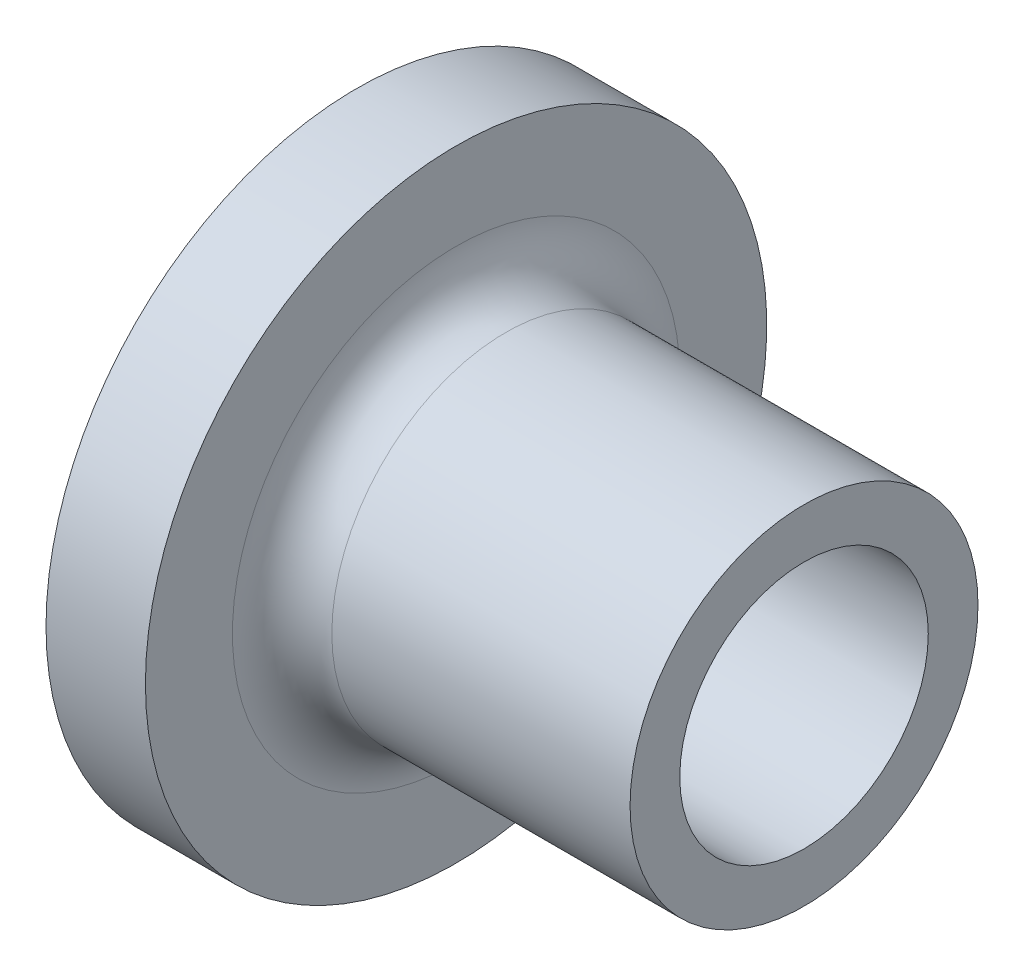
SolidWorks part; units mm, degrees
ref_plane "Front Plane" through (0, 0, 0) normal (0, 0, 1) x (1, 0, 0)
ref_plane "Top Plane" through (0, 0, 0) normal (0, 1, 0) x (1, 0, 0)
ref_plane "Right Plane" through (0, 0, 0) normal (1, 0, 0) x (0, 0, -1)
sketch "Sketch1" plane through (0, 0, 0) normal (0, 0, 1) x (1, 0, 0)
  line L0 (0, 0) -> (5.5, 0) construction
  line L1 (-3.5, 3.5) -> (3.5, 3.5)
  line L2 (-3.5, 3.5) -> (-3.5, 2.5)
  line L3 (-3.5, 2.5) -> (3.5, 2.5)
  line L4 (3.5, 3.5) -> (3.5, 2.5)
  line L5 (-3.5, 2.5) -> (-5.5, 2.5)
  line L6 (-3.5, 2.5) -> (-3.5, 6.25)
  line L7 (-3.5, 6.25) -> (-5.5, 6.25)
  line L8 (-5.5, 2.5) -> (-5.5, 6.25)
  line L9 (3.5, 2.5) -> (5.5, 2.5)
  line L10 (3.5, 2.5) -> (3.5, 6.25)
  line L11 (3.5, 6.25) -> (5.5, 6.25)
  line L12 (5.5, 2.5) -> (5.5, 6.25)
  dimension "D1" = 7
  dimension "D2" = 3.5
  dimension "D3" = 2.5
  dimension "D4" = 1
  dimension "D5" = 2
  dimension "D6" = 2
  dimension "D7" = 6.25
revolve "Revolve1" add sketch "Sketch1" angle 360 about L0
fillet "Fillet1" radius 1 1 edges at (-3.5, 0, 3.5)
